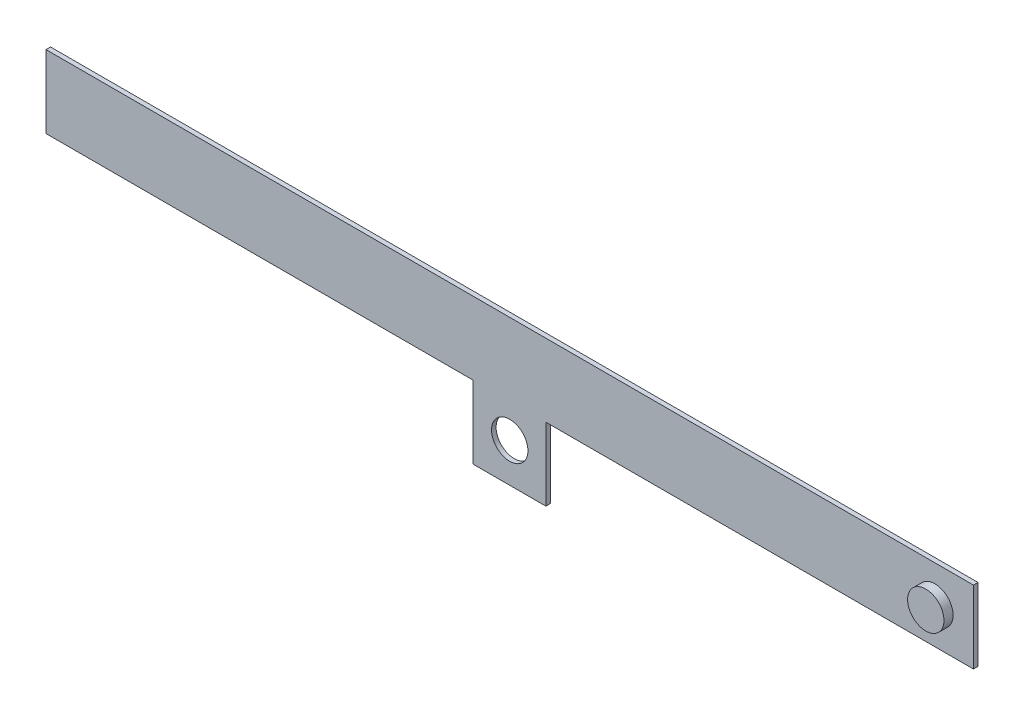
SolidWorks part; units mm, degrees
ref_plane "Front Plane" through (0, 0, 0) normal (0, 0, 1) x (1, 0, 0)
ref_plane "Top Plane" through (0, 0, 0) normal (0, 1, 0) x (1, 0, 0)
ref_plane "Right Plane" through (0, 0, 0) normal (1, 0, 0) x (0, 0, -1)
sketch "Sketch1" plane through (0, 0, 0) normal (0, 0, 1) x (1, 0, 0)
  line L1 (-323.85, -25.4) -> (-25.5467, -25.4)
  line L2 (-323.85, -25.4) -> (-323.85, 25.4)
  line L3 (-323.85, 25.4) -> (323.85, 25.4)
  line L4 (323.85, -25.4) -> (323.85, 25.4)
  line L5 (-323.85, -25.4) -> (323.85, 25.4) construction
  line L6 (-323.85, 25.4) -> (323.85, -25.4) construction
  line L14 (0, 25.4) -> (0, -48.9819) construction
  line L16 (-25.5467, -25.4) -> (-25.5467, -76.2)
  line L17 (-25.5467, -76.2) -> (25.2533, -76.2)
  line L18 (25.2533, -25.4) -> (25.2533, -76.2)
  line L19 (25.2533, -25.4) -> (323.85, -25.4)
  circle A1 centre (0, -48.9819) radius 12.7
  point P0 (0, 0)
  dimension "D3" = 74.3819
  dimension "D5" = 48.9819
  dimension "D8" = 25.4
  dimension "D1" = 50.8
  dimension "D2" = 647.7
  dimension "D4" = 298.3033
  dimension "D6" = 50.8
  dimension "D7" = 50.8
extrude "Boss-Extrude1" add sketch "Sketch1" along normal blind 3.175
sketch "Sketch2" plane through (0, 0, 3.175) normal (0, 0, 1) x (1, 0, 0)
  line L0 (-323.85, 0) -> (323.85, 0) construction
  line L1 (-323.85, 25.4) -> (-323.85, -25.4) construction
  line L2 (323.85, -25.4) -> (323.85, 25.4) construction
  circle A0 centre (296.9144, 0) radius 12.7
  point P25 (11.5858, 0)
  point P26 (0, 0)
  point P27 (-0.1467, 50.8)
  dimension "D1" = 25.4
extrude "Boss-Extrude2" add sketch "Sketch2" along normal blind 6.35
